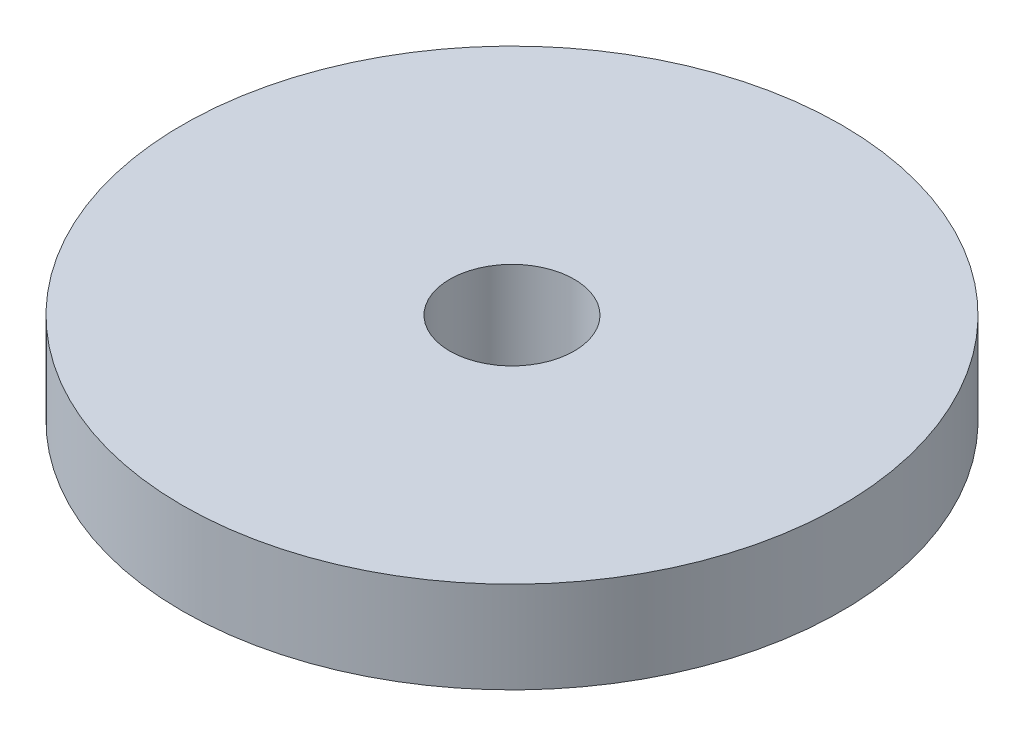
SolidWorks part; units mm, degrees
material "PETG"
ref_plane "Front Plane" through (0, 0, 0) normal (0, 0, 1) x (1, 0, 0)
ref_plane "Top Plane" through (0, 0, 0) normal (0, 1, 0) x (1, 0, 0)
ref_plane "Right Plane" through (0, 0, 0) normal (1, 0, 0) x (0, 0, -1)
sketch "Sketch1" plane through (0, 0, 0) normal (0, 1, 0) x (1, 0, 0)
  circle A0 centre (0, 0) radius 9
  circle A1 centre (0, 0) radius 1.7
  dimension "D1" = 18
  dimension "D2" = 3.4
extrude "Boss-Extrude1" add sketch "Sketch1" along normal blind 2.5
